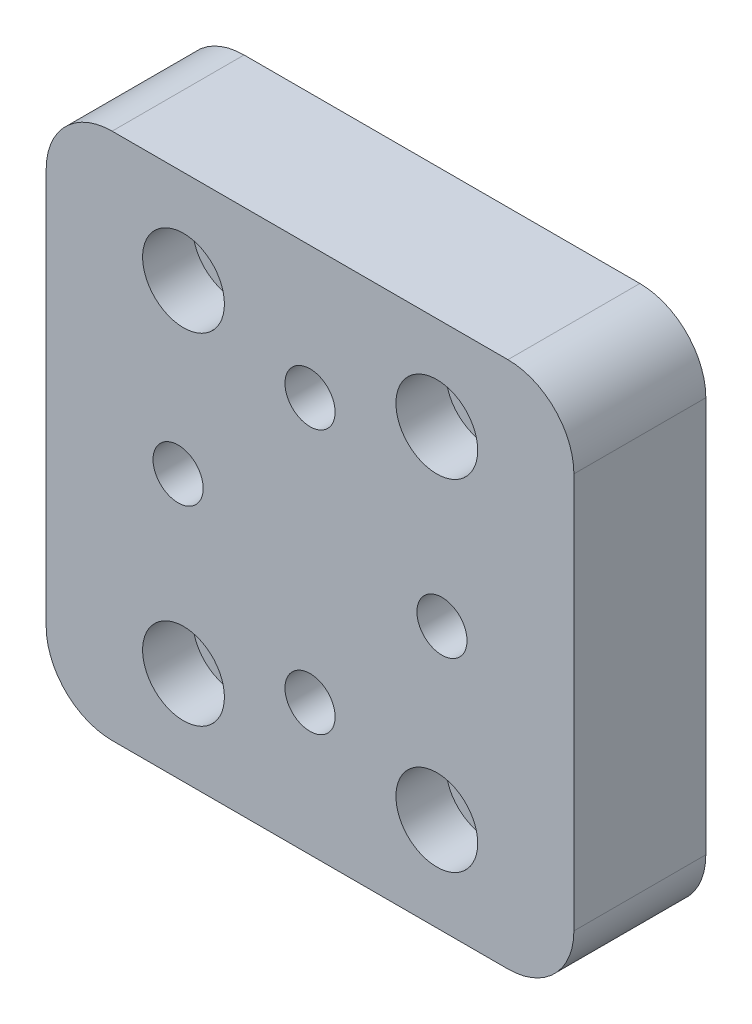
SolidWorks part; units mm, degrees
ref_plane "Front Plane" through (0, 0, 0) normal (0, 0, 1) x (1, 0, 0)
ref_plane "Top Plane" through (0, 0, 0) normal (0, 1, 0) x (1, 0, 0)
ref_plane "Right Plane" through (0, 0, 0) normal (1, 0, 0) x (0, 0, -1)
sketch "Sketch1" plane through (0, 0, 0) normal (0, 0, 1) x (1, 0, 0)
  line L1 (0, 0) -> (50.8, 0)
  line L2 (0, 0) -> (0, -50.8)
  line L3 (0, -50.8) -> (50.8, -50.8)
  line L4 (50.8, 0) -> (50.8, -50.8)
  circle A0 centre (13.2199, -9.017) radius 2.413
  circle A1 centre (37.6039, -9.017) radius 2.413
  circle A2 centre (13.2199, -41.783) radius 2.413
  circle A3 centre (37.6039, -41.783) radius 2.413
  dimension "D5" = 4.826
  dimension "D6" = 4.826
  dimension "D7" = 4.826
  dimension "D8" = 4.826
  dimension "D11" = 24.384
  dimension "D12" = 24.384
  dimension "D1" = 50.8
  dimension "D2" = 50.8
extrude "Boss-Extrude1" add sketch "Sketch1" along normal blind 12.7
sketch "Sketch2" plane through (0, 0, 0) normal (0, 0, -1) x (-1, 0, 0)
  line L0 (0, 0) -> (-50.8, -50.8)
  line L3 (0, -50.8) -> (-50.8, 0)
  line L7 (-24.7562, -24.7562) -> (-26.0438, -24.7562)
  line L8 (-24.7562, -24.7562) -> (-24.7562, -26.0438)
  line L11 (-24.7562, -24.7562) -> (-26.0438, -26.0438) construction
  line L12 (-24.7562, -26.0438) -> (-26.0438, -24.7562) construction
  circle A2 centre (-25.4, -12.7) radius 2.413
  circle A7 centre (-25.4, -38.1) radius 2.413
  circle A8 centre (-38.1, -25.4) radius 2.413
  circle A9 centre (-12.7, -25.4) radius 2.413
  point P12 (-25.4, -25.4)
  dimension "D1" = 4.826
  dimension "D2" = 12.7
  dimension "D3" = 12.7
  dimension "D4" = 12.7
  dimension "D5" = 12.7
extrude "Cut-Extrude2" cut sketch "Sketch2" against normal blind 12.7 contours A8 | A2 | A7 | A9
sketch "Sketch7" plane through (0, 0, 0) normal (0, 0, -1) x (-1, 0, 0)
  line L0 (-25.4, -40.513) -> (-25.4, -35.687)
  line L1 (-10.287, -25.4) -> (-15.113, -25.4)
  line L2 (-35.687, -25.4) -> (-40.513, -25.4)
  line L3 (-25.4, -15.113) -> (-25.4, -10.287)
  line L5 (-25.4, -18.1993) -> (-20.6375, -15.4496)
  line L6 (-20.6375, -15.4496) -> (-20.6375, -9.9504)
  line L7 (-20.6375, -9.9504) -> (-25.4, -7.2007)
  line L8 (-25.4, -7.2007) -> (-30.1625, -9.9504)
  line L9 (-30.1625, -9.9504) -> (-30.1625, -15.4496)
  line L10 (-30.1625, -15.4496) -> (-25.4, -18.1993)
  line L11 (-18.1993, -25.4) -> (-15.4496, -30.1625)
  line L12 (-15.4496, -30.1625) -> (-9.9504, -30.1625)
  line L13 (-9.9504, -30.1625) -> (-7.2007, -25.4)
  line L14 (-7.2007, -25.4) -> (-9.9504, -20.6375)
  line L15 (-9.9504, -20.6375) -> (-15.4496, -20.6375)
  line L16 (-15.4496, -20.6375) -> (-18.1993, -25.4)
  line L17 (-25.4, -32.6007) -> (-30.1625, -35.3504)
  line L18 (-30.1625, -35.3504) -> (-30.1625, -40.8496)
  line L19 (-30.1625, -40.8496) -> (-25.4, -43.5993)
  line L20 (-25.4, -43.5993) -> (-20.6375, -40.8496)
  line L21 (-20.6375, -40.8496) -> (-20.6375, -35.3504)
  line L22 (-20.6375, -35.3504) -> (-25.4, -32.6007)
  line L23 (-32.6007, -25.4) -> (-35.3504, -20.6375)
  line L24 (-35.3504, -20.6375) -> (-40.8496, -20.6375)
  line L25 (-40.8496, -20.6375) -> (-43.5993, -25.4)
  line L26 (-43.5993, -25.4) -> (-40.8496, -30.1625)
  line L27 (-40.8496, -30.1625) -> (-35.3504, -30.1625)
  line L28 (-35.3504, -30.1625) -> (-32.6007, -25.4)
  circle A0 centre (-25.4, -38.1) radius 2.413 construction
  circle A1 centre (-12.7, -25.4) radius 2.413 construction
  circle A2 centre (-38.1, -25.4) radius 2.413 construction
  circle A3 centre (-25.4, -12.7) radius 2.413 construction
  circle A4 centre (-25.4, -12.7) radius 4.7625 construction
  circle A5 centre (-12.7, -25.4) radius 4.7625 construction
  circle A6 centre (-25.4, -38.1) radius 4.7625 construction
  circle A7 centre (-38.1, -25.4) radius 4.7625 construction
  circle M9 centre (-12.7, -25.4) radius 2.413
  circle M10 centre (-25.4, -38.1) radius 2.413
  circle M11 centre (-25.4, -12.7) radius 2.413
  circle M12 centre (-38.1, -25.4) radius 2.413
  dimension "D1" = 9.525
  dimension "D2" = 9.525
  dimension "D3" = 9.525
  dimension "D4" = 9.525
extrude "Cut-Extrude5" cut sketch "Sketch7" against normal blind 6.35 contours L21 L22 L17 L18 L19 L20 M10 | L27 L28 L23 L24 L25 L26 M12 | L15 L16 L11 L12 L13 L14 M9 | L9 L10 L5 L6 L7 L8 M11
sketch "Sketch10" plane through (0, 0, 0) normal (0, 0, -1) x (-1, 0, 0)
  line L0 (-6.35, 0) -> (-44.45, 0)
  line L1 (-50.8, 0) -> (0, 0) construction
  line L2 (0, -44.45) -> (0, -6.35)
  line L3 (0, 0) -> (0, -50.8) construction
  line L4 (-6.35, -50.8) -> (-44.45, -50.8)
  line L5 (0, -50.8) -> (-50.8, -50.8) construction
  line L6 (-50.8, -44.45) -> (-50.8, -6.35)
  line L7 (-50.8, -50.8) -> (-50.8, 0) construction
  line L8 (-50.8, -44.45) -> (-50.6495, -45.8243)
  line L9 (-50.8, -50.8) -> (-44.45, -50.8)
  line L10 (0, -44.45) -> (0, -50.8)
  line L11 (0, -50.8) -> (-6.35, -50.8)
  line L12 (-6.35, -50.8) -> (0, -50.8)
  line L13 (0, -50.8) -> (-6.35, -50.8)
  line L14 (0, -6.35) -> (0, 0)
  line L15 (0, 0) -> (-6.35, 0)
  line L16 (-50.8, -6.35) -> (-50.8, 0)
  line L17 (-50.8, 0) -> (-44.45, 0)
  arc A0 (0, -44.45) -> (-6.35, -50.8) centre (-6.35, -44.45) cw
  arc A1 (-6.35, 0) -> (0, -6.35) centre (-6.35, -6.35) cw
  arc A2 (-50.8, -6.35) -> (-44.45, 0) centre (-44.45, -6.35) cw
  arc A3 (-44.45, -50.8) -> (-50.8, -44.45) centre (-44.45, -44.45) cw
  point P5 (-25.4, 0)
  point P10 (0, -25.4)
  point P17 (-25.4, -50.8)
  point P23 (-50.8, -25.4)
  line M33 (0, -50.8) -> (0, 0)
  line M34 (0, 0) -> (-50.8, 0)
  line M35 (-50.8, 0) -> (-50.8, -50.8)
  line M36 (-50.8, -50.8) -> (0, -50.8)
  dimension "D1" = 38.1
  dimension "D2" = 38.1
  dimension "D3" = 6.35
  dimension "D4" = 6.35
  dimension "D5" = 6.35
  dimension "D6" = 38.1
  dimension "D7" = 6.35
  dimension "D8" = 38.1
  dimension "D9" = 6.35
extrude "Cut-Extrude6" cut sketch "Sketch10" against normal through all contours A2 M35 M34 | A1 M34 M33 | A0 M33 M36 | A3 M36 M35
sketch "Sketch13" plane through (0, 0, 12.7) normal (0, 0, 1) x (1, 0, 0)
  circle A0 centre (37.6039, -41.783) radius 3.937
  circle A1 centre (13.2199, -41.783) radius 3.937
  circle A2 centre (37.6039, -9.017) radius 3.937
  circle A3 centre (13.2199, -9.017) radius 3.937
  dimension "D1" = 7.874
  dimension "D2" = 7.874
extrude "Cut-Extrude7" cut sketch "Sketch13" against normal blind 4.826
